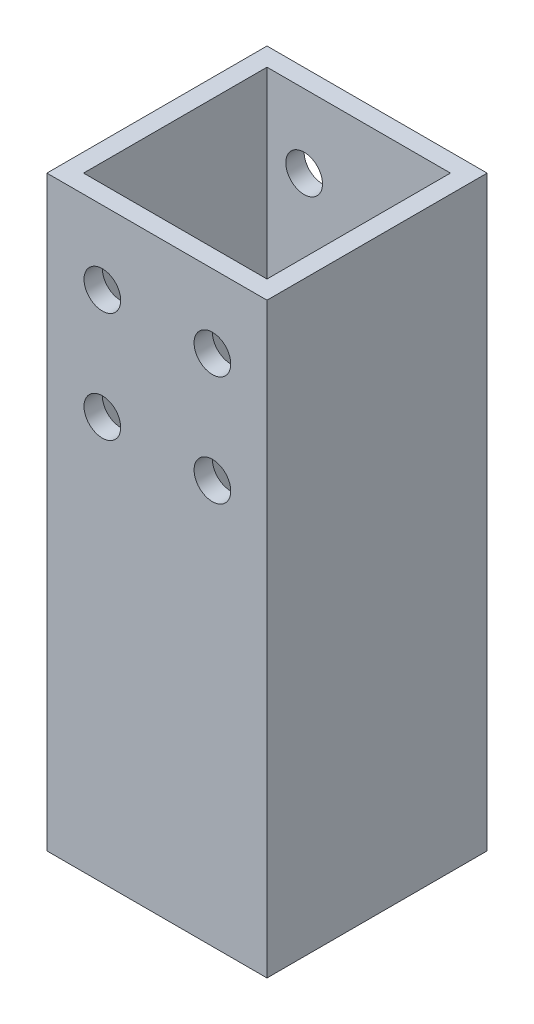
SolidWorks part; units mm, degrees
ref_plane "Front Plane" through (0, 0, 0) normal (0, 0, 1) x (1, 0, 0)
ref_plane "Top Plane" through (0, 0, 0) normal (0, 1, 0) x (1, 0, 0)
ref_plane "Right Plane" through (0, 0, 0) normal (1, 0, 0) x (0, 0, -1)
sketch "Sketch1" plane through (0, 0, 0) normal (0, 1, 0) x (1, 0, 0)
  line L1 (-19.05, -19.05) -> (19.05, -19.05)
  line L2 (-19.05, -19.05) -> (-19.05, 19.05)
  line L3 (-19.05, 19.05) -> (19.05, 19.05)
  line L4 (19.05, -19.05) -> (19.05, 19.05)
  line L5 (-19.05, -19.05) -> (19.05, 19.05) construction
  line L6 (-19.05, 19.05) -> (19.05, -19.05) construction
  line L7 (-15.875, -15.875) -> (15.875, -15.875)
  line L8 (-15.875, -15.875) -> (-15.875, 15.875)
  line L9 (-15.875, 15.875) -> (15.875, 15.875)
  line L10 (15.875, -15.875) -> (15.875, 15.875)
  line L11 (-15.875, -15.875) -> (15.875, 15.875) construction
  line L12 (-15.875, 15.875) -> (15.875, -15.875) construction
  point P0 (0, 0)
  point P6 (0, 0)
  dimension "D1" = 38.1
  dimension "D2" = 38.1
  dimension "D3" = 3.175
extrude "Boss-Extrude1" add sketch "Sketch1" along normal blind 101.6
sketch "Sketch2" plane through (0, 0, 19.05) normal (0, 0, 1) x (1, 0, 0)
  line L0 (-19.05, 101.6) -> (-19.05, 0) construction
  line L2 (-19.05, 0) -> (19.05, 0) construction
  circle A0 centre (-9.4488, 69.85) radius 3.175
  dimension "D1" = 6.35
  dimension "D2" = 9.6012
  dimension "D3" = 69.85
extrude "Cut-Extrude1" cut sketch "Sketch2" against normal blind 101.6
pattern_linear "LPattern1" count 2 spacing 19.05 along (1, 0, 0) count 2 spacing 19.05 along (0, 1, 0) of "Cut-Extrude1"
